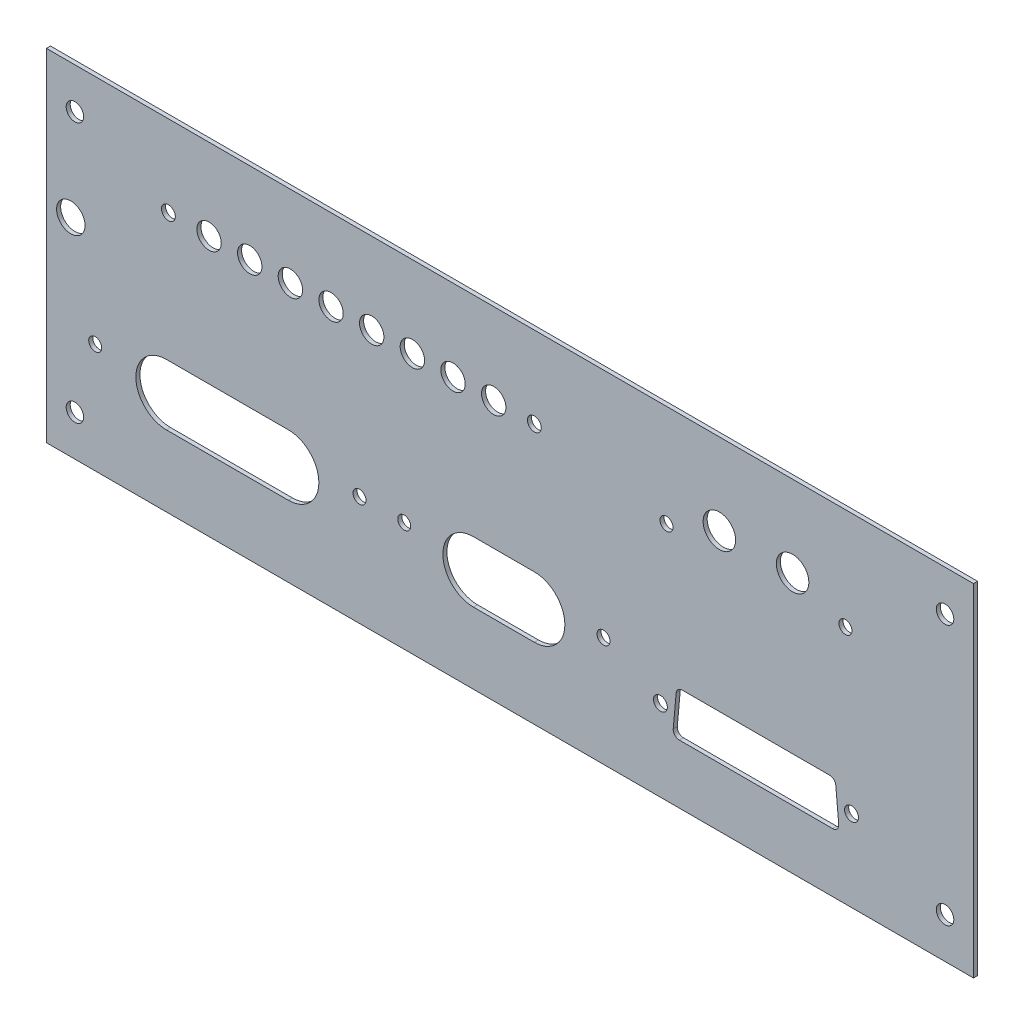
SolidWorks part; units mm, degrees
ref_plane "Спереди" through (0, 0, 0) normal (0, 0, 1) x (1, 0, 0)
ref_plane "Сверху" through (0, 0, 0) normal (0, 1, 0) x (1, 0, 0)
ref_plane "Справа" through (0, 0, 0) normal (1, 0, 0) x (0, 0, -1)
sketch "Эскиз1" plane through (0, 0, 0) normal (0, 0, 1) x (1, 0, 0)
  line L0 (0, 0) -> (58.061, 0) construction
  line L1 (0, 0) -> (0, 47.3035) construction
  line L3 (-114, -42) -> (114, -42)
  line L4 (-114, -42) -> (-114, 42)
  line L5 (-114, 42) -> (114, 42)
  line L6 (114, -42) -> (114, 42)
  circle A8 centre (107, 32) radius 2.15
  circle A9 centre (-107, 32) radius 2.15
  circle A10 centre (-107, -32) radius 2.15
  circle A11 centre (107, -32) radius 2.15
  dimension "D14" = 4.3
  dimension "D15" = 10
  dimension "D16" = 7
  dimension "D1" = 84
  dimension "D2" = 228
extrude "Вытянуть1" add sketch "Эскиз1" along normal blind 1
sketch "Эскиз3" plane through (0, 0, 1) normal (0, 0, 1) x (1, 0, 0)
  line L0 (-47.9981, -22) -> (120.6827, -22) construction
  line L1 (40.1487, -25.8642) -> (40.876, -17.8642)
  line L2 (41.6425, -27.5) -> (79.3575, -27.5)
  line L3 (-114, -42) -> (114, -42) construction
  line L4 (42.3698, -16.5) -> (78.6302, -16.5)
  line L5 (34.3104, 17) -> (86.5925, 17) construction
  line L6 (80.8513, -25.8642) -> (80.124, -17.8642)
  line L7 (60.5, 95.3032) -> (60.5, -77.6913) construction
  line L10 (51.5, 22) -> (68.5193, 22) construction
  line L11 (114, -42) -> (114, 42) construction
  line L12 (114, 42) -> (-114, 42) construction
  circle A0 centre (37, -22) radius 1.7
  circle A1 centre (84, -22) radius 1.7
  arc A2 (41.6425, -27.5) -> (40.1487, -25.8642) centre (41.6425, -26) cw
  arc A3 (42.3698, -16.5) -> (40.876, -17.8642) centre (42.3698, -18) ccw
  arc A4 (80.124, -17.8642) -> (78.6302, -16.5) centre (78.6302, -18) ccw
  arc A5 (79.3575, -27.5) -> (80.8513, -25.8642) centre (79.3575, -26) ccw
  circle A6 centre (38.5, 17) radius 1.6
  circle A7 centre (82.5, 17) radius 1.6
  circle A8 centre (51.5, 22) radius 4
  circle A9 centre (69.5, 22) radius 4
  point P14 (40, -27.5)
  point P17 (41, -16.5)
  point P20 (80, -16.5)
  point P23 (81, -27.5)
  dimension "D4" = 47
  dimension "D5" = 3.4
  dimension "D6" = 1.5
  dimension "D9" = 3.2
  dimension "D11" = 18
  dimension "D12" = 8
  dimension "D13" = 44
  dimension "D14" = 20
  dimension "D8" = 30
  dimension "D1" = 39
  dimension "D2" = 41
  dimension "D3" = 11
  dimension "D7" = 20
  dimension "D10" = 25
extrude "Вырез-Вытянуть1" cut sketch "Эскиз3" against normal blind 10
sketch "Эскиз4" plane through (0, 0, 1) normal (0, 0, 1) x (1, 0, 0)
  line L0 (-114, 42) -> (-114, -42) construction
  line L1 (-114, -42) -> (114, -42) construction
  line L2 (-95.842, -17) -> (24.8302, -17) construction
  line L3 (-84.5, -9.5) -> (-54.5, -9.5)
  line L4 (-84.5, -24.5) -> (-54.5, -24.5)
  line L5 (-69.5, -2.1564) -> (-69.5, -32.5755) construction
  line L6 (-9, -9.5) -> (6, -9.5)
  line L7 (-9, -24.5) -> (6, -24.5)
  line L8 (-1.5, -4.8658) -> (-1.5, -32.5755) construction
  circle A0 centre (-108, 9) radius 3.5
  arc A1 (-84.5, -9.5) -> (-84.5, -24.5) centre (-84.5, -17) ccw
  arc A2 (-54.5, -9.5) -> (-54.5, -24.5) centre (-54.5, -17) cw
  circle A3 centre (-102, -15) radius 1.6
  circle A4 centre (-37, -15) radius 1.6
  arc A5 (-9, -9.5) -> (-9, -24.5) centre (-9, -17) ccw
  arc A6 (6, -9.5) -> (6, -24.5) centre (6, -17) cw
  circle A7 centre (-26, -15) radius 1.6
  circle A8 centre (23, -15) radius 1.6
  dimension "D3" = 7
  dimension "D6" = 15
  dimension "D5" = 30
  dimension "D8" = 2
  dimension "D4" = 11
  dimension "D9" = 3.2
  dimension "D7" = 32.5
  dimension "D13" = 15
  dimension "D14" = 49
  dimension "D15" = 2
  dimension "D11" = 32.5
  dimension "D1" = 6
  dimension "D2" = 51
  dimension "D10" = 25
  dimension "D16" = 15
  dimension "D17" = 88
extrude "Вырез-Вытянуть2" cut sketch "Эскиз4" against normal blind 1
sketch "Эскиз5" plane through (0, 0, 1) normal (0, 0, 1) x (1, 0, 0)
  line L0 (-39, 37.0344) -> (-39, 0) construction
  line L1 (-84, 22) -> (6, 22) construction
  line L2 (114, 42) -> (-114, 42) construction
  line L3 (-114, 42) -> (-114, -42) construction
  circle A0 centre (-84, 22) radius 1.7
  circle A1 centre (6, 22) radius 1.7
  circle A2 centre (-4, 22) radius 3
  circle A3 centre (-14, 22) radius 3
  circle A4 centre (-24, 22) radius 3
  circle A5 centre (-34, 22) radius 3
  circle A6 centre (-44, 22) radius 3
  circle A7 centre (-54, 22) radius 3
  circle A8 centre (-64, 22) radius 3
  circle A9 centre (-74, 22) radius 3
  dimension "D1" = 90
  dimension "D2" = 3.4
  dimension "D5" = 6
  dimension "D3" = 20
  dimension "D4" = 30
  dimension "D6" = 35
extrude "Вырез-Вытянуть3" cut sketch "Эскиз5" against normal blind 10
